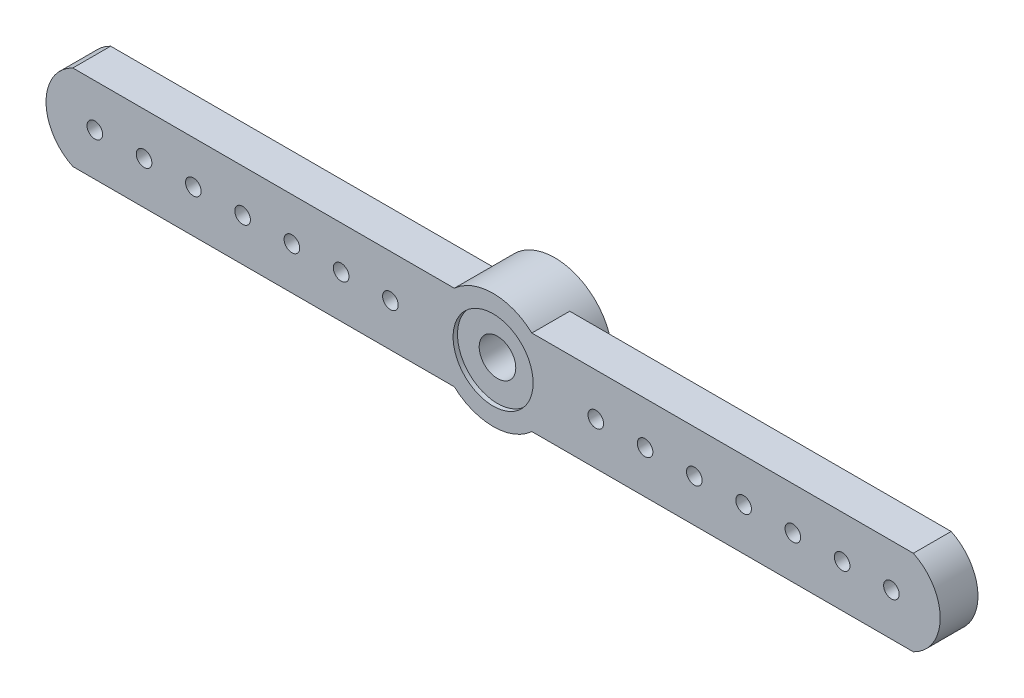
SolidWorks part; units mm, degrees
ref_plane "Front Plane" through (0, 0, 0) normal (0, 0, 1) x (1, 0, 0)
ref_plane "Top Plane" through (0, 0, 0) normal (0, 1, 0) x (1, 0, 0)
ref_plane "Right Plane" through (0, 0, 0) normal (1, 0, 0) x (0, 0, -1)
sketch "Sketch1" plane through (0, 0, 0) normal (0, 0, 1) x (1, 0, 0)
  line L0 (-23.2791, 0) -> (23.2791, 0) construction
  line L1 (-23.2791, 2.2225) -> (23.2791, 2.2225)
  line L2 (-23.2791, 2.2225) -> (-23.2791, -2.2225)
  line L3 (-23.2791, -2.2225) -> (23.2791, -2.2225)
  line L4 (23.2791, 2.2225) -> (23.2791, -2.2225)
  line L5 (0, 0) -> (0, 17.0411) construction
  circle A0 centre (0, 0) radius 3.0035
  arc A1 (-21.8821, 2.2225) -> (-21.8821, -2.2225) centre (-20.8127, 0) ccw
  arc A2 (21.8821, 2.2225) -> (21.8821, -2.2225) centre (20.8127, 0) cw
  dimension "D3" = 6.0071
  dimension "D1" = 4.445
  dimension "D2" = 46.5582
  dimension "D4" = 1.397
extrude "Boss-Extrude1" add sketch "Sketch1" along normal blind 1.9685 contours L3 A0 | L1 A0 L3 | L1 A0 | A2 L1 A0 L3 | L1 A1 L3 A0
sketch "Sketch2" plane through (0, 0, 1.9685) normal (0, 0, 1) x (1, 0, 0)
  line L0 (0, 0) -> (0, 12.9288) construction
  line L1 (-21.1455, 0) -> (-21.1455, 5.6069) construction
  line L2 (-20.3327, 0) -> (-20.3327, 7.4638) construction
  line L4 (-5.7531, 0) -> (-5.7531, 5.7068) construction
  circle A0 centre (-20.7391, 0) radius 0.4064
  arc A1 (21.8821, -2.2225) -> (21.8821, 2.2225) centre (20.8127, 0) ccw construction
  arc A2 (-21.8821, 2.2225) -> (-21.8821, -2.2225) centre (-20.8127, 0) ccw construction
  circle A3 centre (-18.1737, 0) radius 0.4064
  circle A4 centre (-15.6083, 0) radius 0.4064
  circle A5 centre (-13.0429, 0) radius 0.4064
  circle A6 centre (-10.4775, 0) radius 0.4064
  circle A7 centre (-7.9121, 0) radius 0.4064
  circle A8 centre (-5.3467, 0) radius 0.4064
  circle A9 centre (5.3467, 0) radius 0.4064
  circle A10 centre (7.9121, 0) radius 0.4064
  circle A11 centre (10.4775, 0) radius 0.4064
  circle A12 centre (13.0429, 0) radius 0.4064
  circle A13 centre (15.6083, 0) radius 0.4064
  circle A14 centre (18.1737, 0) radius 0.4064
  circle A15 centre (20.7391, 0) radius 0.4064
  point P11 (-23.2791, 0)
  dimension "D1" = 0.8128
  dimension "D2" = 2.1336
  dimension "D4" = 14.5796
  dimension "D3" = 7
extrude "Cut-Extrude1" cut sketch "Sketch2" against normal through all
sketch "Sketch3" plane through (0, 0, 1.9685) normal (0, 0, 1) x (1, 0, 0)
  circle A0 centre (0, 0) radius 2.0828
  dimension "D1" = 4.1656
extrude "Cut-Extrude2" cut sketch "Sketch3" against normal blind 0.2286
sketch "Sketch4" plane through (0, 0, 1.7399) normal (0, 0, 1) x (1, 0, 0)
  circle A0 centre (0, 0) radius 0.9525
  dimension "D1" = 1.905
extrude "Cut-Extrude3" cut sketch "Sketch4" against normal through all
sketch "Sketch5" plane through (0, 0, 0) normal (0, 0, -1) x (-1, 0, 0)
  circle A0 centre (0, 0) radius 3.0035
  circle A1 centre (0, 0) radius 1.7335
  arc A3 (-2.0203, -2.2225) -> (2.0203, -2.2225) centre (0, 0) ccw construction
  dimension "D1" = 1.27
extrude "Boss-Extrude2" add sketch "Sketch5" along normal blind 1.2446
